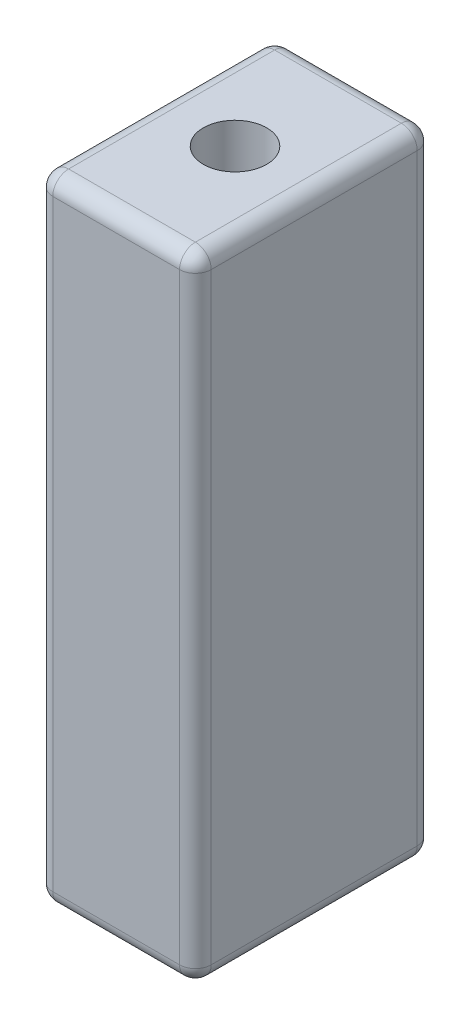
SolidWorks part; units mm, degrees
material "1023 Carbon Steel Sheet (SS)"
ref_plane "Ön Düzlem" through (0, 0, 0) normal (0, 0, 1) x (1, 0, 0)
ref_plane "Üst Düzlem" through (0, 0, 0) normal (0, 1, 0) x (1, 0, 0)
ref_plane "Sağ Düzlem" through (0, 0, 0) normal (1, 0, 0) x (0, 0, -1)
sketch "Sketch1" plane through (0, 0, 0) normal (0, 0, 1) x (1, 0, 0)
  line L0 (0, 0) -> (0, 80)
  line L1 (0, 80) -> (20, 80)
  line L2 (20, 80) -> (20, 0)
  line L3 (20, 0) -> (0, 0)
  dimension "D1" = 80
  dimension "D2" = 20
extrude "Boss-Extrude1" add sketch "Sketch1" along normal blind 30 contours L0 L1 L2 L3
fillet "Fillet1" radius 2 12 edges at (0, 40, 0) (10, 0, 0) (0, 0, 15) (10, 0, 30) (20, 0, 15) (20, 40, 0) (20, 80, 15) (10, 80, 0) (0, 80, 15) (0, 40, 30) (20, 40, 30) (10, 80, 30)
sketch "Sketch2" plane through (0, 80, 0) normal (0, 1, 0) x (1, 0, 0)
  line L1 (0, -28) -> (0, -2) construction
  line L2 (18, -30) -> (2, -30) construction
  circle A0 centre (10, -15) radius 4
  point P6 (0, 0)
  dimension "D1" = 10
  dimension "D3" = 8
  dimension "D2" = 15
extrude "Cut-Extrude1" cut sketch "Sketch2" against normal blind 10
sketch "Sketch3" plane through (0, 0, 0) normal (0, -1, 0) x (1, 0, 0)
  line L0 (0, 2) -> (0, 28) construction
  line L1 (18, 0) -> (2, 0) construction
  circle A0 centre (10, 15) radius 4
  dimension "D1" = 10
  dimension "D3" = 8
  dimension "D2" = 15
extrude "Cut-Extrude2" cut sketch "Sketch3" against normal blind 10
